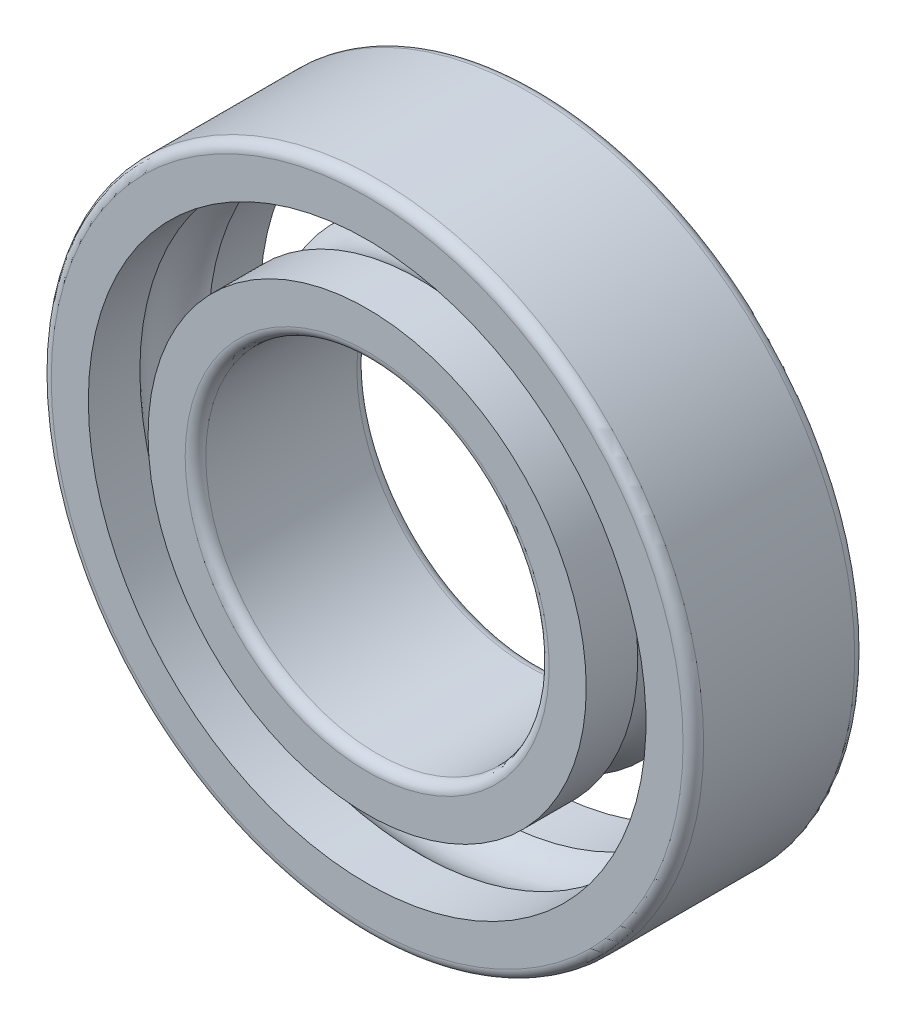
SolidWorks part; units mm, degrees
material "1.4000 (X6Cr13)"
ref_plane "前视基准面" through (0, 0, 0) normal (0, 0, 1) x (1, 0, 0)
ref_plane "上视基准面" through (0, 0, 0) normal (0, 1, 0) x (1, 0, 0)
ref_plane "右视基准面" through (0, 0, 0) normal (1, 0, 0) x (0, 0, -1)
sketch "草图1" plane through (0, 0, 0) normal (0, 1, 0) x (1, 0, 0)
  line L0 (6.38, -2.5) -> (6.38, -0.9994)
  line L1 (5, 2.5) -> (6.38, 2.5)
  line L2 (5, 2.5) -> (5, -2.5)
  line L3 (5, -2.5) -> (6.38, -2.5)
  line L4 (9.5, 2.5) -> (9.5, -2.5)
  line L5 (8.12, 2.5) -> (8.12, 0.9994)
  line L6 (6.38, 0.9994) -> (6.38, 2.5)
  line L7 (8.12, -0.9994) -> (8.12, -2.5)
  line L8 (0, 11.486) -> (0, -11.486) construction
  line L9 (8.12, 2.5) -> (9.5, 2.5)
  line L10 (8.12, -2.5) -> (9.5, -2.5)
  arc A0 (6.38, 0.9994) -> (6.38, -0.9994) centre (7.25, 0) ccw
  arc A1 (8.12, -0.9994) -> (8.12, 0.9994) centre (7.25, 0) ccw
  point P0 (7.25, 0)
  point P19 (0, 0)
  dimension "D4" = 2.65
  dimension "D1" = 5
  dimension "D2" = 9.5
  dimension "D3" = 5
  dimension "D5" = 7.25
  dimension "D6" = 1.38
  dimension "D7" = 1.38
  dimension "D8" = 2.5
  dimension "D9" = 0
revolve "旋转1" add sketch "草图1" angle 360 about L8
fillet "圆角1" radius 0.3 2 edges at (-9.5, 0, -2.5) (-9.5, 0, 2.5)
fillet "圆角2" radius 0.3 2 edges at (-5, 0, 2.5) (-5, 0, -2.5)
